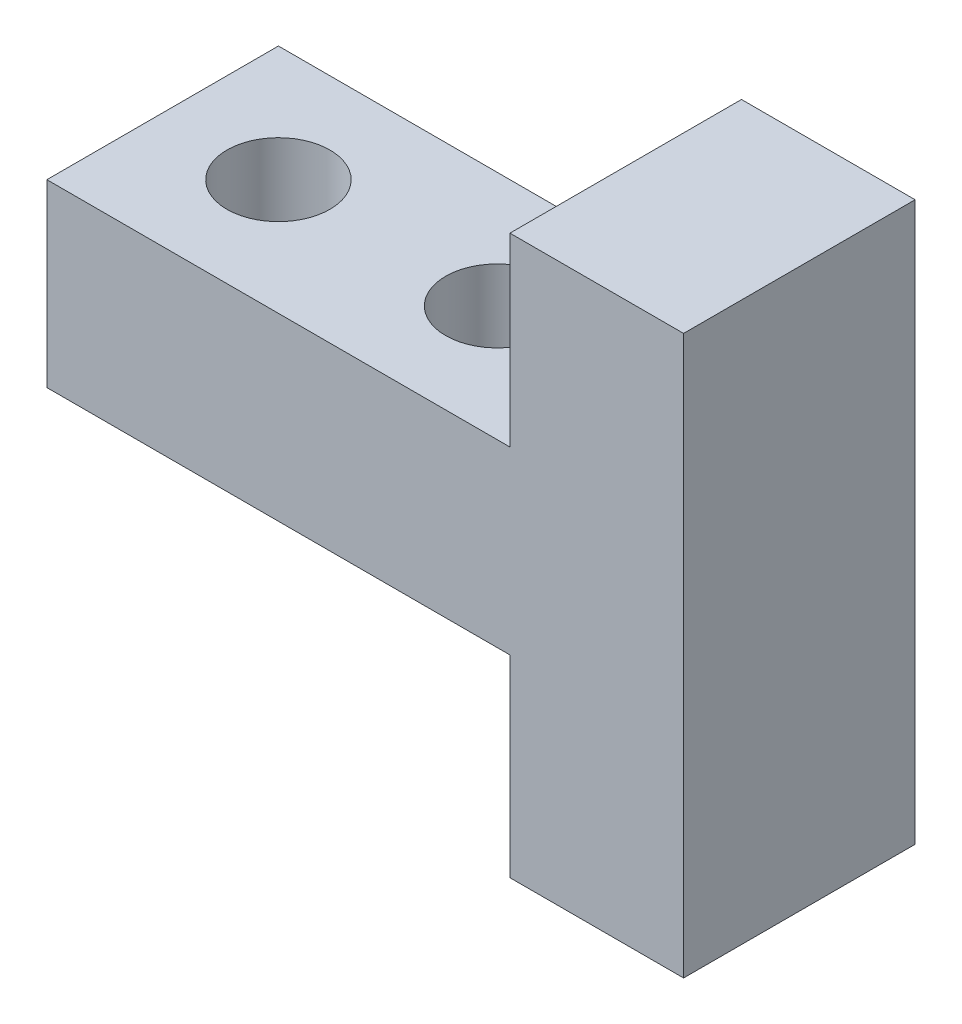
SolidWorks part; units mm, degrees
ref_plane "Plane1" through (0, 0, 0) normal (0, 0, 1) x (1, 0, 0)
ref_plane "Plane2" through (0, 0, 0) normal (0, 1, 0) x (1, 0, 0)
ref_plane "Plane3" through (0, 0, 0) normal (1, 0, 0) x (0, 0, -1)
sketch "sk-body" plane through (0, 0, 0) normal (0, 0, 1) x (1, 0, 0)
  line L0 (-13.5, 28.4) -> (0, 28.4)
  line L1 (0, 28.4) -> (0, -15)
  line L2 (0, -15) -> (-13.5, -15)
  line L3 (-13.5, -15) -> (-13.5, 0)
  line L4 (-13.5, 0) -> (-49.5, 0)
  line L5 (-49.5, 0) -> (-49.5, 14)
  line L6 (-49.5, 14) -> (-13.5, 14)
  line L7 (-13.5, 14) -> (-13.5, 28.4)
  dimension "D1" = 14.4
  dimension "D2" = 49.5
  dimension "D3" = 14
  dimension "D4" = 13.5
  dimension "D5" = 43.4
extrude "body" add sketch "sk-body" along normal mid plane 18
sketch "sk-hole_v" plane through (0, 14, 0) normal (0, 1, 0) x (-1, 0, 0)
  line L0 (10.3751, 0) -> (-10.3751, 0) construction
  line L1 (49.5, 9) -> (49.5, -9) construction
  circle A0 centre (40.5, 0) radius 4
  circle A1 centre (23.5, 0) radius 4
  dimension "v" = 8
  dimension "x" = 9
  dimension "y" = 17
extrude "hole_v" cut sketch "sk-hole_v" against normal through all
sketch "Sketch1" plane through (0, 0, 9) normal (0, 0, 1) x (1, 0, 0)
  line L1 (-49.5, 14) -> (-49.5, 0) construction
  line L2 (-49.5, 14) -> (-49.5, 0) construction
  circle A0 centre (-40.5, 7) radius 4
  circle A1 centre (-23.5, 7) radius 4
  point P6 (-49.5, 7)
  dimension "D1" = 8
  dimension "D3" = 17
  dimension "D2" = 9
extrude "Hole_Side" [suppressed] cut sketch "Sketch1" against normal through all
sketch "Sketch3" [suppressed] plane through (-15.5, 0, 0) normal (-1, 0, 0) x (0, 0, 1)
  line L0 (0, -0.8) -> (0, 18.7) construction
  line L2 (5, 18.7) -> (-5, 18.7) construction
  line L3 (5, 8.95) -> (0, 8.95) construction
  line L5 (5, 17.9) -> (5, 0) construction
  circle A0 centre (0, 13.95) radius 2
  circle A1 centre (0, 3.95) radius 2
  dimension "D1" = 8
  dimension "D2" = 24
extrude "Flat-Mounts" [suppressed] cut sketch "Sketch3" against normal blind 16
sketch "Sketch4" plane through (0, 0, 9) normal (0, 0, 1) x (1, 0, 0)
  line L1 (-49.5, 10) -> (-43.5, 10)
  line L2 (-49.5, 10) -> (-49.5, 4)
  line L3 (-49.5, 4) -> (-43.5, 4)
  line L4 (-43.5, 10) -> (-43.5, 4)
  line L5 (-49.5, 7) -> (0, 7) construction
  line L7 (-49.5, 14) -> (-49.5, 0) construction
  dimension "D1" = 6
  dimension "D2" = 6
extrude "Flat-Notch" [suppressed] cut sketch "Sketch4" against normal through all
sketch "Sketch5" plane through (0, 0, 9) normal (0, 0, 1) x (1, 0, 0)
  line L0 (-49.5, 0) -> (-13.5, 0) construction
  line L1 (-49.5, 14) -> (-13.5, 14)
  line L2 (-49.5, 14) -> (-49.5, 1)
  line L3 (-49.5, 1) -> (-13.5, 1)
  line L4 (-13.5, 14) -> (-13.5, 1)
  dimension "D1" = 1
extrude "X51" [suppressed] add sketch "Sketch5" against normal up to surface (8 mm away) contours L2 L3 L4 L1
sketch "Sketch6" [suppressed] plane through (-21.15, 0, 0) normal (-1, 0, 0) x (0, 0, 1)
  line L0 (0, 0) -> (0, 2.5) construction
  line L1 (4, 0) -> (-4, 0) construction
  line L2 (0, 2.5) -> (0, 9.5) construction
  circle A0 centre (0, 2.5) radius 1.5
  circle A1 centre (0, 9.5) radius 1.5
  dimension "D3" = 1
  dimension "D1" = 1
  dimension "D2" = 1
extrude "X51_HOLES" [suppressed] cut sketch "Sketch6" against normal blind 1
